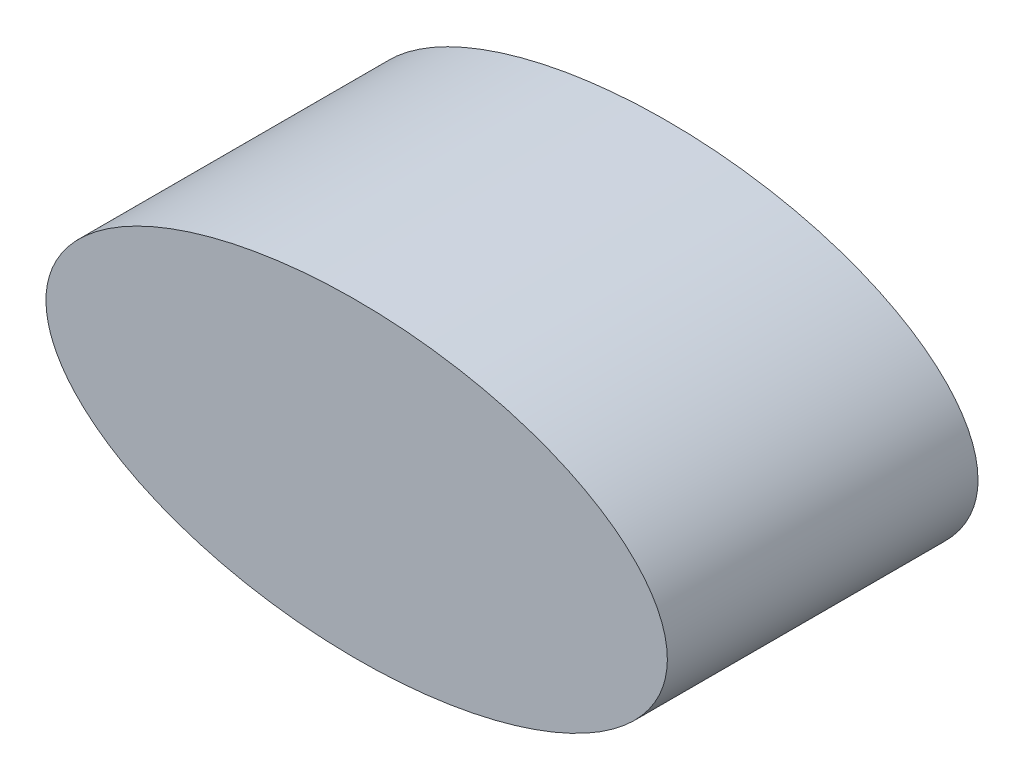
SolidWorks part; units mm, degrees
ref_plane "Front Plane" through (0, 0, 0) normal (0, 0, 1) x (1, 0, 0)
ref_plane "Top Plane" through (0, 0, 0) normal (0, 1, 0) x (1, 0, 0)
ref_plane "Right Plane" through (0, 0, 0) normal (1, 0, 0) x (0, 0, -1)
sketch "Sketch1" plane through (0, 0, 0) normal (0, 0, 1) x (1, 0, 0)
  ellipse E0 centre (20, 15) end of major axis (25, 15) minor radius 2.5
  point P1 (0, 0)
  point P9 (1.5131, 0.9528)
  dimension "D1" = 20
  dimension "D2" = 15
  dimension "D3" = 10
  dimension "D4" = 5
extrude "Boss-Extrude1" add sketch "Sketch1" along normal blind 5
